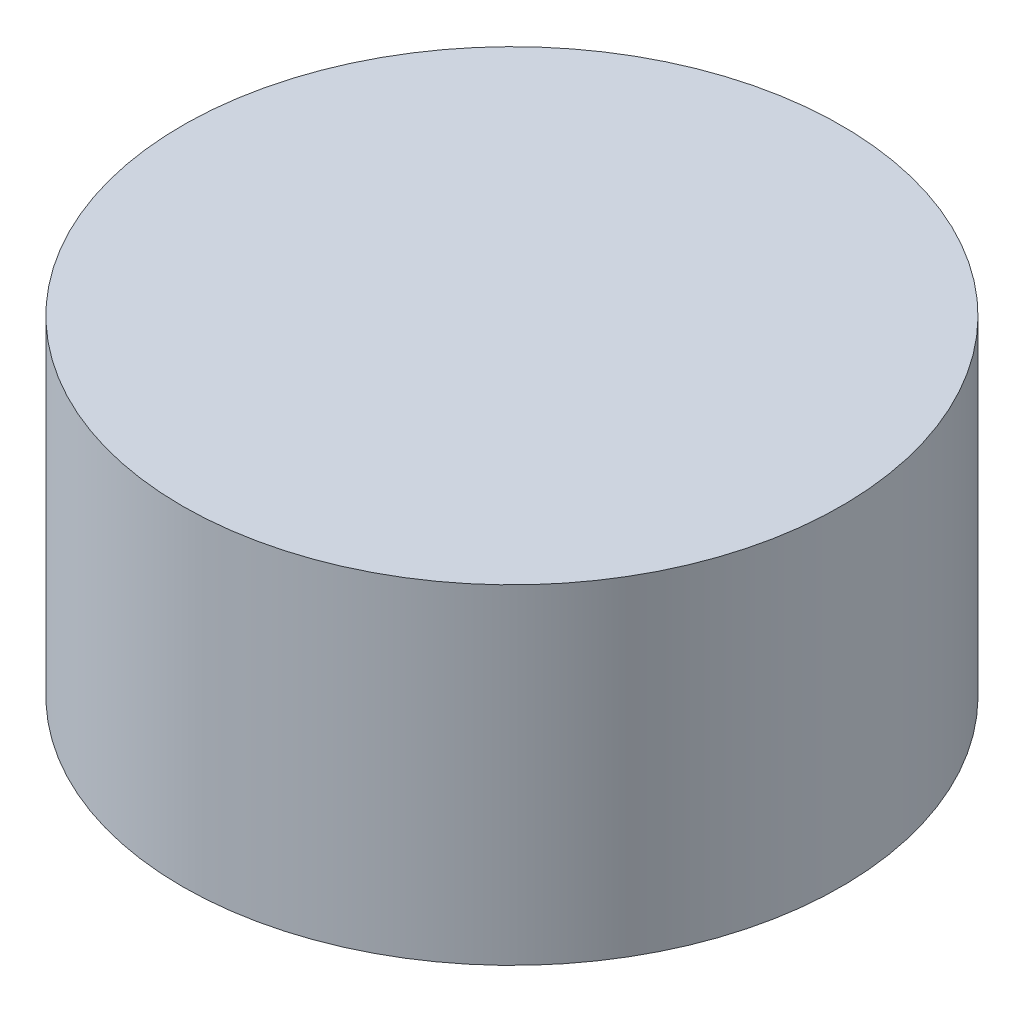
SolidWorks part; units mm, degrees
ref_plane "Front Plane" through (0, 0, 0) normal (0, 0, 1) x (1, 0, 0)
ref_plane "Top Plane" through (0, 0, 0) normal (0, 1, 0) x (1, 0, 0)
ref_plane "Right Plane" through (0, 0, 0) normal (1, 0, 0) x (0, 0, -1)
sketch "Sketch1" plane through (0, 0, 0) normal (0, 1, 0) x (1, 0, 0)
  circle A0 centre (0, 0) radius 4
  dimension "D1" = 8
extrude "Boss-Extrude1" add sketch "Sketch1" along normal mid plane 4
sketch "Sketch2" plane through (0, 2, 0) normal (0, 1, 0) x (1, 0, 0)
  point P0 (0, 0)
